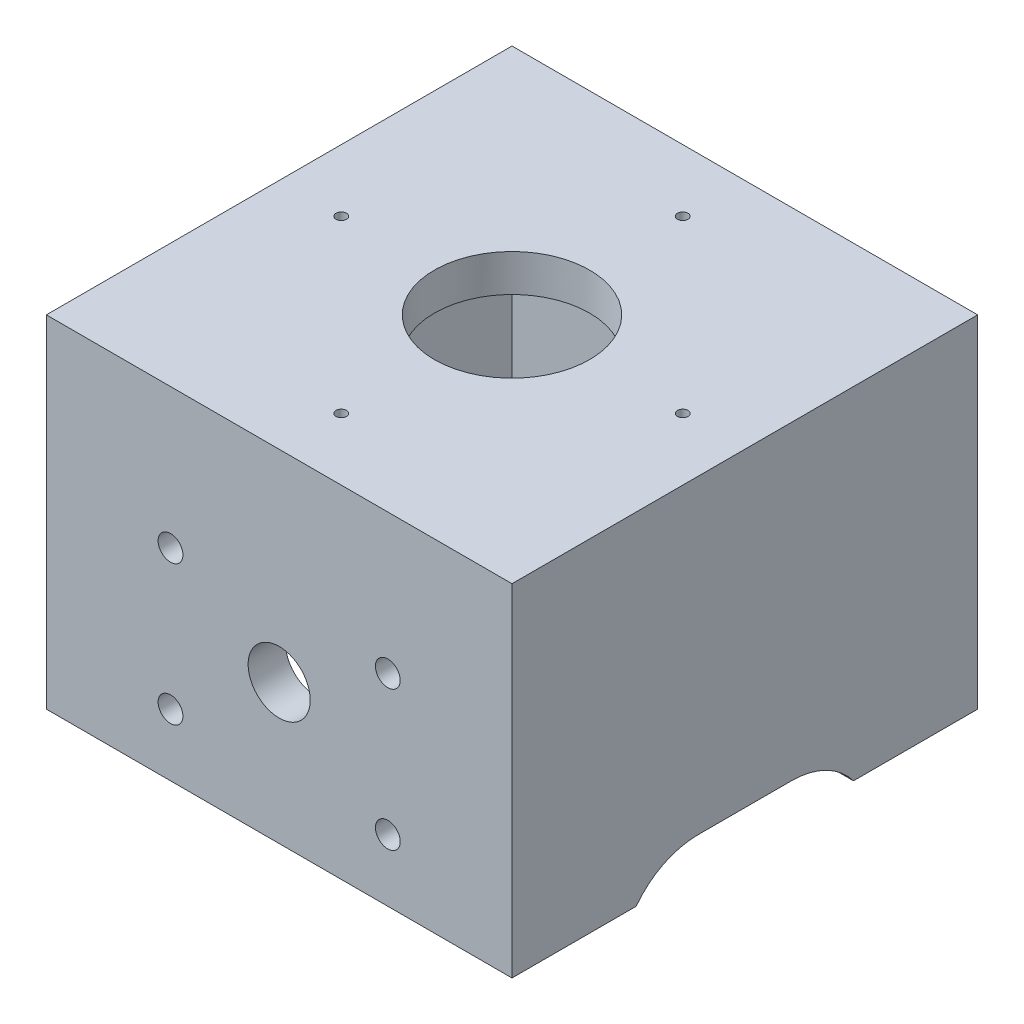
SolidWorks part; units mm, degrees
material "Teak"
ref_plane "Front Plane" through (0, 0, 0) normal (0, 0, 1) x (1, 0, 0)
ref_plane "Top Plane" through (0, 0, 0) normal (0, 1, 0) x (1, 0, 0)
ref_plane "Right Plane" through (0, 0, 0) normal (1, 0, 0) x (0, 0, -1)
sketch "Sketch1" plane through (0, 0, 0) normal (0, 1, 0) x (1, 0, 0)
  line L1 (0, 0) -> (150, 0)
  line L2 (0, 0) -> (0, 150)
  line L3 (0, 150) -> (150, 150)
  line L4 (150, 0) -> (150, 150)
  dimension "D1" = 150
  dimension "D2" = 150
extrude "Boss-Extrude1" add sketch "Sketch1" along normal blind 110
sketch "Sketch3" plane through (0, 0, 0) normal (0, -1, 0) x (1, 0, 0)
  line L14 (12, -138) -> (138, -138)
  line L15 (138, -138) -> (138, -12)
  line L16 (12, -12) -> (12, -138)
  line L17 (138, -12) -> (12, -12)
  line L18 (12, -138) -> (138, -138)
  line L19 (138, -138) -> (138, -12)
  line L20 (12, -12) -> (12, -138)
  line L21 (138, -12) -> (12, -12)
  dimension "D1" = 12
extrude "Cut-Extrude1" cut sketch "Sketch3" against normal offset from surface (98 mm away) 12 up to face at (75, 110, -75)
sketch "Sketch4" plane through (0, 110, 0) normal (0, 1, 0) x (1, 0, 0)
  line L0 (150, 0) -> (150, 150) construction
  line L1 (150, 150) -> (0, 150) construction
  line L2 (0, 150) -> (0, 0) construction
  circle A0 centre (75, 75) radius 55
  circle A1 centre (75, 130) radius 1.7
  circle A2 centre (130, 75) radius 1.7
  circle A3 centre (75, 20) radius 1.7
  circle A4 centre (20, 75) radius 1.7
  circle A5 centre (75, 75) radius 25
  point P4 (150, 75)
  point P7 (75, 150)
  point P12 (0, 75)
  dimension "D1" = 110
  dimension "D2" = 3.4
  dimension "D4" = 50
  dimension "D3" = 4
extrude "Cut-Extrude2" cut sketch "Sketch4" against normal through all contours A2 | A1 | A4 | A3 | A5
sketch "Sketch6" plane through (0, 0, 0) normal (-1, 0, 0) x (0, 0, 1)
  line L1 (0, 110) -> (0, 0) construction
  line L14 (-150, 0) -> (0, 0) construction
  line L15 (-75, 110) -> (-75, 0) construction
  line L16 (-150, 110) -> (0, 110) construction
  line L20 (-90, 10) -> (-60, 10)
  line L21 (-40, 0) -> (-110, 0)
  arc A2 (-110, 0) -> (-90, 10) centre (-90, -15) cw
  arc A3 (-40, 0) -> (-60, 10) centre (-60, -15) ccw
  dimension "D3" = 40
  dimension "D1" = 25
  dimension "D2" = 10
extrude "Cut-Extrude3" cut sketch "Sketch6" against normal through all
sketch "Sketch7" plane through (0, 0, 0) normal (0, 0, -1) x (-1, 0, 0)
  line L1 (-150, 110) -> (-150, 0) construction
  line L3 (0, 0) -> (-150, 0) construction
  line L5 (0, 110) -> (-150, 110) construction
  line L15 (-75, 110) -> (-75, 0) construction
  line L20 (-90, 10) -> (-60, 10)
  line L21 (-40, 0) -> (-110, 0)
  arc A2 (-110, 0) -> (-90, 10) centre (-90, -15) cw
  arc A3 (-40, 0) -> (-60, 10) centre (-60, -15) ccw
  point P13 (-75, 110)
  dimension "D3" = 40
  dimension "D1" = 25
  dimension "D2" = 10
extrude "Cut-Extrude4" cut sketch "Sketch7" against normal up to surface (12 mm away) from surface at 150 up to face at (75, 49, -138) starting at face at (75, 55, -150)
sketch "Sketch5" plane through (0, 0, 0) normal (0, 0, 1) x (1, 0, 0)
  line L0 (0, 110) -> (0, 0) construction
  line L1 (150, 110) -> (150, 0) construction
  line L2 (0, 110) -> (150, 110) construction
  line L4 (75, 90) -> (75, 0) construction
  line L5 (0, 90) -> (150, 90) construction
  line L8 (0, 0) -> (150, 0) construction
  circle A0 centre (40, 65) radius 4
  circle A1 centre (75, 45) radius 10
  circle A2 centre (110, 65) radius 4
  circle A3 centre (40, 20) radius 4
  circle A4 centre (110, 20) radius 4
  point P13 (75, 110)
  point P14 (75, 45)
  point P20 (75, 90)
  point P21 (0, 0)
  point P25 (0, 0)
  point P26 (0, 0)
  dimension "D1" = 8
  dimension "D2" = 20
  dimension "D3" = 8
  dimension "D7" = 8
  dimension "D9" = 8
  dimension "D4" = 40
  dimension "D5" = 40
  dimension "D6" = 25
  dimension "D8" = 20
  dimension "D10" = 20
extrude "Cut-Extrude5" cut sketch "Sketch5" against normal up to surface (12 mm away) up to face at (75, 49, -12)
